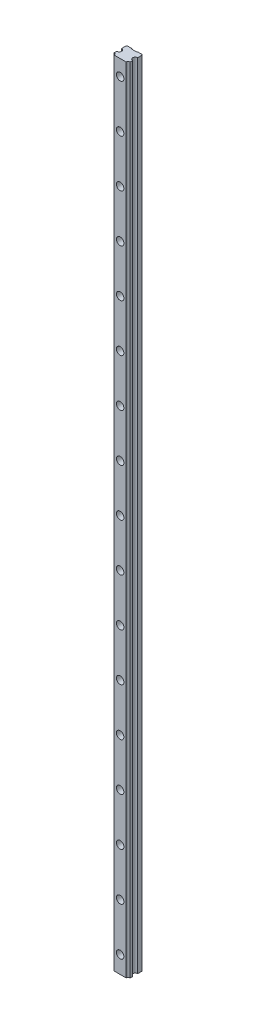
SolidWorks part; units mm, degrees
ref_plane "Plano frontal" through (0, 0, 0) normal (0, 0, 1) x (1, 0, 0)
ref_plane "Plano superior" through (0, 0, 0) normal (0, 1, 0) x (1, 0, 0)
ref_plane "Plano direito" through (0, 0, 0) normal (1, 0, 0) x (0, 0, -1)
sketch "Esboço1" plane through (0, 0, 0) normal (0, 1, 0) x (1, 0, 0)
  line L0 (-10.048, -3.265) -> (-10.048, -6.485)
  line L1 (-9.048, 9.315) -> (-3.563, 9.315)
  line L2 (-10.048, 8.315) -> (-10.048, 2.935)
  line L3 (-7.6458, -8.985) -> (7.652, -8.985)
  line L4 (10.152, 8.315) -> (10.152, 2.935)
  line L5 (-3.563, 8.585) -> (3.667, 8.585)
  line L6 (9.152, 9.315) -> (10.152, 8.315)
  line L7 (-3.563, 9.315) -> (-3.563, 8.585)
  line L8 (-10.048, 8.315) -> (-9.048, 9.315)
  line L10 (-10.048, -6.485) -> (-9.6458, -6.485)
  line L13 (3.667, 8.585) -> (3.667, 9.315)
  line L14 (7.652, -8.985) -> (7.652, -8.485)
  line L16 (3.667, 9.315) -> (9.152, 9.315)
  line L17 (10.152, -3.265) -> (10.152, -6.485)
  line L18 (9.652, -6.485) -> (10.152, -6.485)
  line L22 (-7.6458, -8.485) -> (-7.6458, -8.985)
  arc A0 (-10.048, -3.265) -> (-10.048, 2.935) centre (-10.048, -0.165) ccw
  arc A1 (10.152, 2.935) -> (10.152, -3.265) centre (10.152, -0.165) ccw
  arc A2 (-7.6458, -8.485) -> (-9.6458, -6.485) centre (-9.6458, -8.485) ccw
  arc A3 (9.652, -6.485) -> (7.652, -8.485) centre (9.652, -8.485) ccw
  point P0 (-10.048, 9.315)
  point P3 (10.152, 9.315)
  point P26 (7.652, -6.485)
  dimension "D3" = 1
  dimension "D13" = 2
  dimension "D14" = 2
  dimension "D2" = 20.2
  dimension "D4" = 7.23
  dimension "D5" = 6.38
  dimension "D6" = 1
  dimension "D7" = 2.5
  dimension "D8" = 2.5
  dimension "D9" = 3.22
  dimension "D10" = 17.57
  dimension "D11" = 1
  dimension "D12" = 1
extrude "Ressalto-extrusão1" add sketch "Esboço1" against normal blind 1000
sketch "Esboço2" plane through (0, 0, -8.585) normal (0, 0, -1) x (-1, 0, 0)
  line L0 (0, 0) -> (0, -1046.3519) construction
  circle A0 centre (0, -19.745) radius 2.87
  circle A1 centre (0, -79.655) radius 2.87
  circle A2 centre (0, -139.565) radius 2.87
  circle A3 centre (0, -199.475) radius 2.87
  circle A4 centre (0, -259.385) radius 2.87
  circle A5 centre (0, -319.295) radius 2.87
  circle A6 centre (0, -379.205) radius 2.87
  circle A7 centre (0, -439.115) radius 2.87
  circle A8 centre (0, -499.025) radius 2.87
  circle A9 centre (0, -558.935) radius 2.87
  circle A10 centre (0, -618.845) radius 2.87
  circle A11 centre (0, -678.755) radius 2.87
  circle A12 centre (0, -738.665) radius 2.87
  circle A13 centre (0, -798.575) radius 2.87
  circle A14 centre (0, -858.485) radius 2.87
  circle A15 centre (0, -918.395) radius 2.87
  circle A16 centre (0, -978.305) radius 2.87
  dimension "D1" = 5.74
  dimension "D3" = 17
  dimension "D4" = 59.91
  dimension "D2" = 19.745
extrude "Corte-extrusão1" cut sketch "Esboço2" against normal up to surface (17.57 mm away) up to face at (0.0031, -500, 8.985)
sketch "Esboço3" plane through (0, 0, 8.985) normal (0, 0, 1) x (1, 0, 0)
  line L0 (-7.6458, 0) -> (7.652, 0) construction
  line L1 (0.0031, 0) -> (0.0031, -29.4649) construction
  circle A0 centre (0.0031, -19.745) radius 4.715
  circle A1 centre (0.0031, -79.645) radius 4.715
  circle A2 centre (0.0031, -139.545) radius 4.715
  circle A3 centre (0.0031, -199.445) radius 4.715
  circle A4 centre (0.0031, -259.345) radius 4.715
  circle A5 centre (0.0031, -319.245) radius 4.715
  circle A6 centre (0.0031, -379.145) radius 4.715
  circle A7 centre (0.0031, -439.045) radius 4.715
  circle A8 centre (0.0031, -498.945) radius 4.715
  circle A9 centre (0.0031, -558.845) radius 4.715
  circle A10 centre (0.0031, -618.745) radius 4.715
  circle A11 centre (0.0031, -678.645) radius 4.715
  circle A12 centre (0.0031, -738.545) radius 4.715
  circle A13 centre (0.0031, -798.445) radius 4.715
  circle A14 centre (0.0031, -858.345) radius 4.715
  circle A15 centre (0.0031, -918.245) radius 4.715
  circle A16 centre (0.0031, -978.145) radius 4.715
  dimension "D1" = 19.745
  dimension "D3" = 17
  dimension "D2" = 9.43
extrude "Corte-extrusão2" cut sketch "Esboço3" against normal blind 8.49
